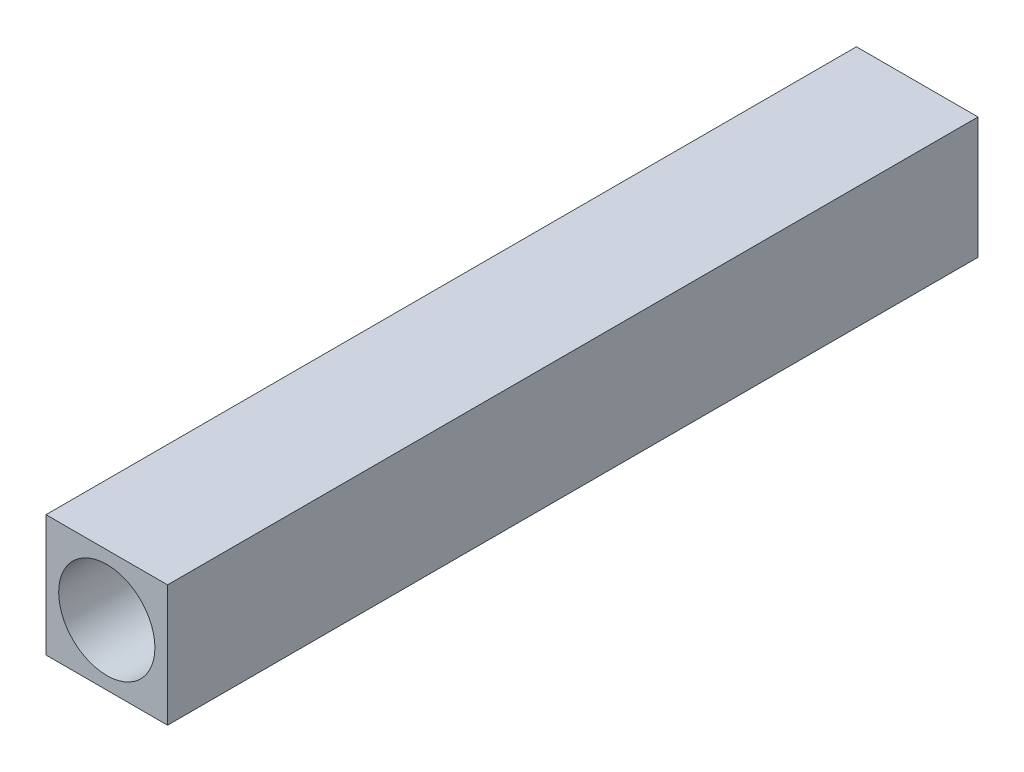
SolidWorks part; units mm, degrees
material "PET"
ref_plane "Front Plane" through (0, 0, 0) normal (0, 0, 1) x (1, 0, 0)
ref_plane "Top Plane" through (0, 0, 0) normal (0, 1, 0) x (1, 0, 0)
ref_plane "Right Plane" through (0, 0, 0) normal (1, 0, 0) x (0, 0, -1)
sketch "Sketch1" plane through (0, 0, 0) normal (0, 0, 1) x (1, 0, 0)
  circle A0 centre (0, 0) radius 9.652
  circle A1 centre (0, 0) radius 12.192
  dimension "D1" = 19.304
  dimension "D2" = 24.384
extrude "Main Inner Tube" add sketch "Sketch1" along normal blind 162.56
sketch "Sketch3" plane through (0, 0, 0) normal (0, 0, -1) x (-1, 0, 0)
  circle A0 centre (0, 0) radius 8.636
  circle A1 centre (0, 0) radius 9.652
  circle A2 centre (0, 0) radius 9.652 construction
  dimension "D1" = 17.272
extrude "Inner Blocking Lip" add sketch "Sketch3" against normal blind 6.35
sketch "Sketch6" plane through (0, 0, 162.56) normal (0, 0, 1) x (1, 0, 0)
  line L1 (-12.192, 12.192) -> (12.192, 12.192)
  line L2 (-12.192, 12.192) -> (-12.192, -12.192)
  line L3 (-12.192, -12.192) -> (12.192, -12.192)
  line L4 (12.192, 12.192) -> (12.192, -12.192)
  circle A0 centre (0, 0) radius 12.192 construction
  circle A1 centre (0, 0) radius 9.652
  circle A2 centre (0, 0) radius 9.652 construction
extrude "Rectangle Outside" add sketch "Sketch6" against normal through all
